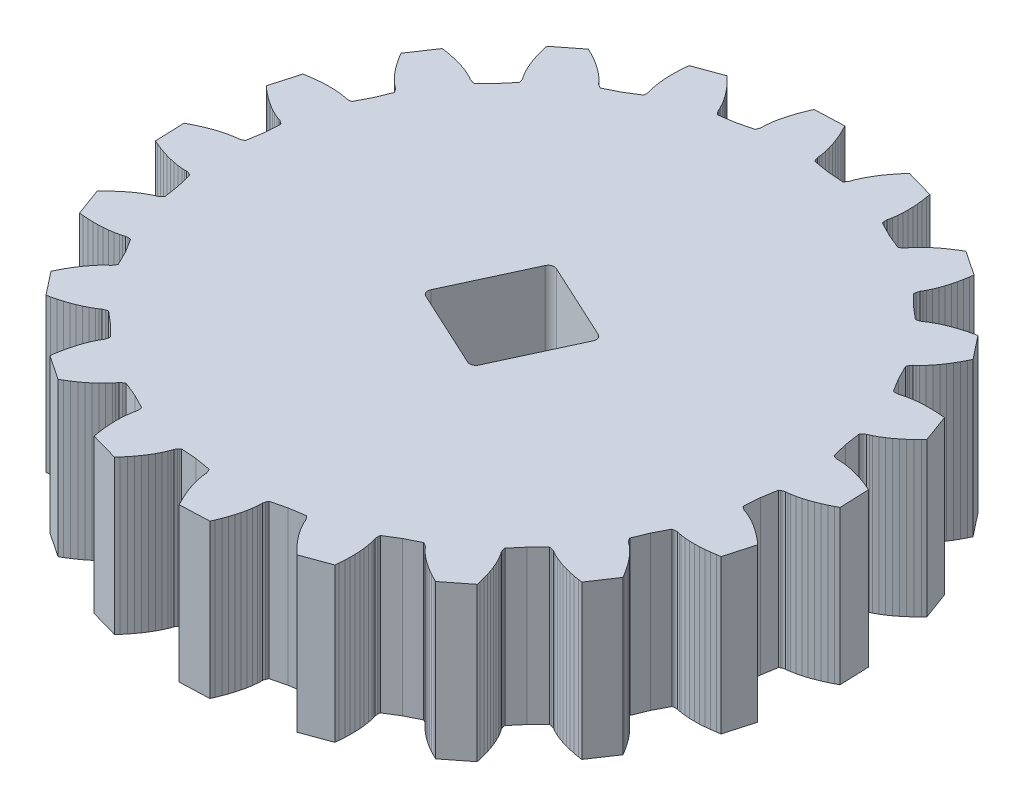
SolidWorks part; units mm, degrees
ref_plane "Front Plane" through (0, 0, 0) normal (0, 0, 1) x (1, 0, 0)
ref_plane "Top Plane" through (0, 0, 0) normal (0, 1, 0) x (1, 0, 0)
ref_plane "Right Plane" through (0, 0, 0) normal (1, 0, 0) x (0, 0, -1)
sketch "Sketch5" plane through (0, 0, 0) normal (0, 1, 0) x (1, 0, 0)
  line L0 (19.9342, 9.6525) -> (19.896, 9.1377)
  line L1 (19.896, 9.1377) -> (19.9282, 9.104)
  line L2 (19.9282, 9.104) -> (19.9619, 9.0786)
  line L3 (19.9619, 9.0786) -> (20.0304, 9.0343)
  line L4 (20.0304, 9.0343) -> (20.1028, 9.0113)
  line L5 (20.1028, 9.0113) -> (20.1744, 8.9841)
  line L6 (20.1744, 8.9841) -> (20.3158, 8.9208)
  line L7 (20.3158, 8.9208) -> (20.4552, 8.8477)
  line L8 (20.4552, 8.8477) -> (20.5926, 8.7663)
  line L9 (20.5926, 8.7663) -> (20.7283, 8.6773)
  line L10 (20.7283, 8.6773) -> (20.862, 8.5813)
  line L11 (20.862, 8.5813) -> (20.9939, 8.4788)
  line L12 (20.9939, 8.4788) -> (21.1239, 8.37)
  line L13 (21.1239, 8.37) -> (21.22, 8.2845)
  line L14 (21.22, 8.2845) -> (20.9572, 7.3582)
  line L15 (20.9572, 7.3582) -> (20.8305, 7.336)
  line L16 (20.8305, 7.336) -> (20.6628, 7.3117)
  line L17 (20.6628, 7.3117) -> (20.4967, 7.2937)
  line L18 (20.4967, 7.2937) -> (20.3325, 7.2823)
  line L19 (20.3325, 7.2823) -> (20.1703, 7.2778)
  line L20 (20.1703, 7.2778) -> (20.0105, 7.2806)
  line L21 (20.0105, 7.2806) -> (19.8536, 7.2916)
  line L22 (19.8536, 7.2916) -> (19.7, 7.312)
  line L23 (19.7, 7.312) -> (19.6248, 7.3265)
  line L24 (19.6248, 7.3265) -> (19.5511, 7.3449)
  line L25 (19.5511, 7.3449) -> (19.4696, 7.3432)
  line L26 (19.4696, 7.3432) -> (19.4275, 7.3393)
  line L27 (19.4275, 7.3393) -> (19.3824, 7.3276)
  line L28 (19.3824, 7.3276) -> (19.1446, 6.8694)
  line L29 (19.1446, 6.8694) -> (18.9491, 6.3916)
  line L30 (18.9491, 6.3916) -> (18.9694, 6.3497)
  line L31 (18.9694, 6.3497) -> (18.9936, 6.3151)
  line L32 (18.9936, 6.3151) -> (19.0451, 6.2518)
  line L33 (19.0451, 6.2518) -> (19.1068, 6.2075)
  line L34 (19.1068, 6.2075) -> (19.1665, 6.1596)
  line L35 (19.1665, 6.1596) -> (19.2814, 6.0556)
  line L36 (19.2814, 6.0556) -> (19.3914, 5.9431)
  line L37 (19.3914, 5.9431) -> (19.4969, 5.8231)
  line L38 (19.4969, 5.8231) -> (19.5984, 5.6966)
  line L39 (19.5984, 5.6966) -> (19.696, 5.564)
  line L40 (19.696, 5.564) -> (19.7898, 5.4257)
  line L41 (19.7898, 5.4257) -> (19.8797, 5.2821)
  line L42 (19.8797, 5.2821) -> (19.9447, 5.1711)
  line L43 (19.9447, 5.1711) -> (19.4086, 4.3714)
  line L44 (19.4086, 4.3714) -> (19.2812, 4.3893)
  line L45 (19.2812, 4.3893) -> (19.1141, 4.418)
  line L46 (19.1141, 4.418) -> (18.9506, 4.4523)
  line L47 (18.9506, 4.4523) -> (18.7909, 4.4922)
  line L48 (18.7909, 4.4922) -> (18.6353, 4.538)
  line L49 (18.6353, 4.538) -> (18.4843, 4.5901)
  line L50 (18.4843, 4.5901) -> (18.3384, 4.649)
  line L51 (18.3384, 4.649) -> (18.1986, 4.7159)
  line L52 (18.1986, 4.7159) -> (18.1316, 4.7529)
  line L53 (18.1316, 4.7529) -> (18.0671, 4.7932)
  line L54 (18.0671, 4.7932) -> (17.9891, 4.8167)
  line L55 (17.9891, 4.8167) -> (17.9479, 4.826)
  line L56 (17.9479, 4.826) -> (17.9014, 4.8289)
  line L57 (17.9014, 4.8289) -> (17.5336, 4.4666)
  line L58 (17.5336, 4.4666) -> (17.2001, 4.0726)
  line L59 (17.2001, 4.0726) -> (17.2064, 4.0264)
  line L60 (17.2064, 4.0264) -> (17.2187, 3.986)
  line L61 (17.2187, 3.986) -> (17.2481, 3.91)
  line L62 (17.2481, 3.91) -> (17.2931, 3.8488)
  line L63 (17.2931, 3.8488) -> (17.3351, 3.7847)
  line L64 (17.3351, 3.7847) -> (17.4123, 3.6504)
  line L65 (17.4123, 3.6504) -> (17.4821, 3.5093)
  line L66 (17.4821, 3.5093) -> (17.5454, 3.3626)
  line L67 (17.5454, 3.3626) -> (17.6028, 3.2109)
  line L68 (17.6028, 3.2109) -> (17.6546, 3.0547)
  line L69 (17.6546, 3.0547) -> (17.7011, 2.8942)
  line L70 (17.7011, 2.8942) -> (17.7423, 2.7298)
  line L71 (17.7423, 2.7298) -> (17.7698, 2.6041)
  line L72 (17.7698, 2.6041) -> (17.0127, 2.0092)
  line L73 (17.0127, 2.0092) -> (16.8971, 2.0657)
  line L74 (16.8971, 2.0657) -> (16.7471, 2.1446)
  line L75 (16.7471, 2.1446) -> (16.6022, 2.2277)
  line L76 (16.6022, 2.2277) -> (16.4626, 2.315)
  line L77 (16.4626, 2.315) -> (16.3288, 2.4066)
  line L78 (16.3288, 2.4066) -> (16.2013, 2.5029)
  line L79 (16.2013, 2.5029) -> (16.0807, 2.604)
  line L80 (16.0807, 2.604) -> (15.9684, 2.7108)
  line L81 (15.9684, 2.7108) -> (15.9161, 2.7667)
  line L82 (15.9161, 2.7667) -> (15.8673, 2.8249)
  line L83 (15.8673, 2.8249) -> (15.8003, 2.8715)
  line L84 (15.8003, 2.8715) -> (15.764, 2.893)
  line L85 (15.764, 2.893) -> (15.7207, 2.9101)
  line L86 (15.7207, 2.9101) -> (15.2589, 2.6792)
  line L87 (15.2589, 2.6792) -> (14.82, 2.4075)
  line L88 (14.82, 2.4075) -> (14.8117, 2.3617)
  line L89 (14.8117, 2.3617) -> (14.811, 2.3194)
  line L90 (14.811, 2.3194) -> (14.8155, 2.238)
  line L91 (14.8155, 2.238) -> (14.8393, 2.1659)
  line L92 (14.8393, 2.1659) -> (14.8594, 2.092)
  line L93 (14.8594, 2.092) -> (14.8913, 1.9404)
  line L94 (14.8913, 1.9404) -> (14.9141, 1.7847)
  line L95 (14.9141, 1.7847) -> (14.929, 1.6256)
  line L96 (14.929, 1.6256) -> (14.9367, 1.4636)
  line L97 (14.9367, 1.4636) -> (14.9377, 1.299)
  line L98 (14.9377, 1.299) -> (14.9323, 1.132)
  line L99 (14.9323, 1.132) -> (14.9207, 0.9629)
  line L100 (14.9207, 0.9629) -> (14.908, 0.8349)
  line L101 (14.908, 0.8349) -> (14.0042, 0.503)
  line L102 (14.0042, 0.503) -> (13.9117, 0.5925)
  line L103 (13.9117, 0.5925) -> (13.7934, 0.7139)
  line L104 (13.7934, 0.7139) -> (13.6813, 0.8377)
  line L105 (13.6813, 0.8377) -> (13.5755, 0.9638)
  line L106 (13.5755, 0.9638) -> (13.4766, 1.0924)
  line L107 (13.4766, 1.0924) -> (13.385, 1.2233)
  line L108 (13.385, 1.2233) -> (13.3016, 1.3568)
  line L109 (13.3016, 1.3568) -> (13.2278, 1.493)
  line L110 (13.2278, 1.493) -> (13.1953, 1.5623)
  line L111 (13.1953, 1.5623) -> (13.1669, 1.6328)
  line L112 (13.1669, 1.6328) -> (13.1176, 1.6977)
  line L113 (13.1176, 1.6977) -> (13.0897, 1.7294)
  line L114 (13.0897, 1.7294) -> (13.0538, 1.7591)
  line L115 (13.0538, 1.7591) -> (12.5433, 1.6822)
  line L116 (12.5433, 1.6822) -> (12.0419, 1.5595)
  line L117 (12.0419, 1.5595) -> (12.0199, 1.5184)
  line L118 (12.0199, 1.5184) -> (12.0061, 1.4785)
  line L119 (12.0061, 1.4785) -> (11.9852, 1.3996)
  line L120 (11.9852, 1.3996) -> (11.9856, 1.3237)
  line L121 (11.9856, 1.3237) -> (11.9819, 1.2472)
  line L122 (11.9819, 1.2472) -> (11.9654, 1.0932)
  line L123 (11.9654, 1.0932) -> (11.9389, 0.938)
  line L124 (11.9389, 0.938) -> (11.9039, 0.7821)
  line L125 (11.9039, 0.7821) -> (11.8612, 0.6256)
  line L126 (11.8612, 0.6256) -> (11.8113, 0.4688)
  line L127 (11.8113, 0.4688) -> (11.7546, 0.3116)
  line L128 (11.7546, 0.3116) -> (11.6913, 0.1544)
  line L129 (11.6913, 0.1544) -> (11.6396, 0.0366)
  line L130 (11.6396, 0.0366) -> (10.6775, 0.0003)
  line L131 (10.6775, 0.0003) -> (10.6172, 0.1139)
  line L132 (10.6172, 0.1139) -> (10.5422, 0.2659)
  line L133 (10.5422, 0.2659) -> (10.4738, 0.4183)
  line L134 (10.4738, 0.4183) -> (10.4122, 0.571)
  line L135 (10.4122, 0.571) -> (10.3578, 0.7238)
  line L136 (10.3578, 0.7238) -> (10.3111, 0.8766)
  line L137 (10.3111, 0.8766) -> (10.2731, 1.0293)
  line L138 (10.2731, 1.0293) -> (10.245, 1.1817)
  line L139 (10.245, 1.1817) -> (10.2356, 1.2577)
  line L140 (10.2356, 1.2577) -> (10.2303, 1.3335)
  line L141 (10.2303, 1.3335) -> (10.2035, 1.4105)
  line L142 (10.2035, 1.4105) -> (10.1867, 1.4492)
  line L143 (10.1867, 1.4492) -> (10.1617, 1.4885)
  line L144 (10.1617, 1.4885) -> (9.6525, 1.5732)
  line L145 (9.6525, 1.5732) -> (9.1377, 1.6114)
  line L146 (9.1377, 1.6114) -> (9.104, 1.5791)
  line L147 (9.104, 1.5791) -> (9.0786, 1.5454)
  line L148 (9.0786, 1.5454) -> (9.0343, 1.4769)
  line L149 (9.0343, 1.4769) -> (9.0113, 1.4045)
  line L150 (9.0113, 1.4045) -> (8.9841, 1.3329)
  line L151 (8.9841, 1.3329) -> (8.9208, 1.1915)
  line L152 (8.9208, 1.1915) -> (8.8477, 1.0522)
  line L153 (8.8477, 1.0522) -> (8.7663, 0.9147)
  line L154 (8.7663, 0.9147) -> (8.6773, 0.7791)
  line L155 (8.6773, 0.7791) -> (8.5813, 0.6453)
  line L156 (8.5813, 0.6453) -> (8.4788, 0.5134)
  line L157 (8.4788, 0.5134) -> (8.37, 0.3835)
  line L158 (8.37, 0.3835) -> (8.2845, 0.2873)
  line L159 (8.2845, 0.2873) -> (7.3582, 0.5501)
  line L160 (7.3582, 0.5501) -> (7.336, 0.6769)
  line L161 (7.336, 0.6769) -> (7.3117, 0.8446)
  line L162 (7.3117, 0.8446) -> (7.2937, 1.0107)
  line L163 (7.2937, 1.0107) -> (7.2823, 1.1749)
  line L164 (7.2823, 1.1749) -> (7.2778, 1.337)
  line L165 (7.2778, 1.337) -> (7.2806, 1.4968)
  line L166 (7.2806, 1.4968) -> (7.2916, 1.6538)
  line L167 (7.2916, 1.6538) -> (7.312, 1.8074)
  line L168 (7.312, 1.8074) -> (7.3265, 1.8825)
  line L169 (7.3265, 1.8825) -> (7.3449, 1.9563)
  line L170 (7.3449, 1.9563) -> (7.3432, 2.0378)
  line L171 (7.3432, 2.0378) -> (7.3393, 2.0798)
  line L172 (7.3393, 2.0798) -> (7.3276, 2.1249)
  line L173 (7.3276, 2.1249) -> (6.8694, 2.3628)
  line L174 (6.8694, 2.3628) -> (6.3916, 2.5582)
  line L175 (6.3916, 2.5582) -> (6.3497, 2.5379)
  line L176 (6.3497, 2.5379) -> (6.3151, 2.5137)
  line L177 (6.3151, 2.5137) -> (6.2518, 2.4622)
  line L178 (6.2518, 2.4622) -> (6.2075, 2.4005)
  line L179 (6.2075, 2.4005) -> (6.1596, 2.3408)
  line L180 (6.1596, 2.3408) -> (6.0556, 2.2259)
  line L181 (6.0556, 2.2259) -> (5.9431, 2.116)
  line L182 (5.9431, 2.116) -> (5.8231, 2.0104)
  line L183 (5.8231, 2.0104) -> (5.6966, 1.9089)
  line L184 (5.6966, 1.9089) -> (5.564, 1.8113)
  line L185 (5.564, 1.8113) -> (5.4257, 1.7176)
  line L186 (5.4257, 1.7176) -> (5.2821, 1.6276)
  line L187 (5.2821, 1.6276) -> (5.1711, 1.5626)
  line L188 (5.1711, 1.5626) -> (4.3714, 2.0987)
  line L189 (4.3714, 2.0987) -> (4.3893, 2.2262)
  line L190 (4.3893, 2.2262) -> (4.418, 2.3932)
  line L191 (4.418, 2.3932) -> (4.4523, 2.5567)
  line L192 (4.4523, 2.5567) -> (4.4922, 2.7164)
  line L193 (4.4922, 2.7164) -> (4.538, 2.872)
  line L194 (4.538, 2.872) -> (4.5901, 3.0231)
  line L195 (4.5901, 3.0231) -> (4.649, 3.169)
  line L196 (4.649, 3.169) -> (4.7159, 3.3087)
  line L197 (4.7159, 3.3087) -> (4.7529, 3.3758)
  line L198 (4.7529, 3.3758) -> (4.7932, 3.4402)
  line L199 (4.7932, 3.4402) -> (4.8167, 3.5183)
  line L200 (4.8167, 3.5183) -> (4.826, 3.5595)
  line L201 (4.826, 3.5595) -> (4.8289, 3.606)
  line L202 (4.8289, 3.606) -> (4.4666, 3.9737)
  line L203 (4.4666, 3.9737) -> (4.0726, 4.3073)
  line L204 (4.0726, 4.3073) -> (4.0264, 4.3009)
  line L205 (4.0264, 4.3009) -> (3.986, 4.2886)
  line L206 (3.986, 4.2886) -> (3.91, 4.2592)
  line L207 (3.91, 4.2592) -> (3.8488, 4.2142)
  line L208 (3.8488, 4.2142) -> (3.7847, 4.1723)
  line L209 (3.7847, 4.1723) -> (3.6504, 4.0951)
  line L210 (3.6504, 4.0951) -> (3.5093, 4.0253)
  line L211 (3.5093, 4.0253) -> (3.3626, 3.9619)
  line L212 (3.3626, 3.9619) -> (3.2109, 3.9045)
  line L213 (3.2109, 3.9045) -> (3.0547, 3.8527)
  line L214 (3.0547, 3.8527) -> (2.8942, 3.8063)
  line L215 (2.8942, 3.8063) -> (2.7298, 3.7651)
  line L216 (2.7298, 3.7651) -> (2.6041, 3.7376)
  line L217 (2.6041, 3.7376) -> (2.0092, 4.4946)
  line L218 (2.0092, 4.4946) -> (2.0657, 4.6102)
  line L219 (2.0657, 4.6102) -> (2.1446, 4.7602)
  line L220 (2.1446, 4.7602) -> (2.2277, 4.9051)
  line L221 (2.2277, 4.9051) -> (2.315, 5.0447)
  line L222 (2.315, 5.0447) -> (2.4066, 5.1785)
  line L223 (2.4066, 5.1785) -> (2.5029, 5.3061)
  line L224 (2.5029, 5.3061) -> (2.604, 5.4266)
  line L225 (2.604, 5.4266) -> (2.7108, 5.5389)
  line L226 (2.7108, 5.5389) -> (2.7667, 5.5912)
  line L227 (2.7667, 5.5912) -> (2.8249, 5.64)
  line L228 (2.8249, 5.64) -> (2.8715, 5.707)
  line L229 (2.8715, 5.707) -> (2.893, 5.7433)
  line L230 (2.893, 5.7433) -> (2.9101, 5.7867)
  line L231 (2.9101, 5.7867) -> (2.6792, 6.2484)
  line L232 (2.6792, 6.2484) -> (2.4075, 6.6874)
  line L233 (2.4075, 6.6874) -> (2.3617, 6.6956)
  line L234 (2.3617, 6.6956) -> (2.3194, 6.6963)
  line L235 (2.3194, 6.6963) -> (2.238, 6.6919)
  line L236 (2.238, 6.6919) -> (2.1659, 6.668)
  line L237 (2.1659, 6.668) -> (2.092, 6.6479)
  line L238 (2.092, 6.6479) -> (1.9404, 6.616)
  line L239 (1.9404, 6.616) -> (1.7847, 6.5932)
  line L240 (1.7847, 6.5932) -> (1.6256, 6.5783)
  line L241 (1.6256, 6.5783) -> (1.4636, 6.5706)
  line L242 (1.4636, 6.5706) -> (1.299, 6.5696)
  line L243 (1.299, 6.5696) -> (1.132, 6.575)
  line L244 (1.132, 6.575) -> (0.9629, 6.5866)
  line L245 (0.9629, 6.5866) -> (0.8349, 6.5993)
  line L246 (0.8349, 6.5993) -> (0.503, 7.5031)
  line L247 (0.503, 7.5031) -> (0.5925, 7.5957)
  line L248 (0.5925, 7.5957) -> (0.7139, 7.7139)
  line L249 (0.7139, 7.7139) -> (0.8377, 7.8261)
  line L250 (0.8377, 7.8261) -> (0.9638, 7.9318)
  line L251 (0.9638, 7.9318) -> (1.0924, 8.0308)
  line L252 (1.0924, 8.0308) -> (1.2233, 8.1224)
  line L253 (1.2233, 8.1224) -> (1.3568, 8.2057)
  line L254 (1.3568, 8.2057) -> (1.493, 8.2795)
  line L255 (1.493, 8.2795) -> (1.5623, 8.312)
  line L256 (1.5623, 8.312) -> (1.6328, 8.3405)
  line L257 (1.6328, 8.3405) -> (1.6977, 8.3897)
  line L258 (1.6977, 8.3897) -> (1.7294, 8.4176)
  line L259 (1.7294, 8.4176) -> (1.7591, 8.4536)
  line L260 (1.7591, 8.4536) -> (1.6822, 8.9641)
  line L261 (1.6822, 8.9641) -> (1.5595, 9.4655)
  line L262 (1.5595, 9.4655) -> (1.5184, 9.4875)
  line L263 (1.5184, 9.4875) -> (1.4785, 9.5012)
  line L264 (1.4785, 9.5012) -> (1.3996, 9.5222)
  line L265 (1.3996, 9.5222) -> (1.3237, 9.5217)
  line L266 (1.3237, 9.5217) -> (1.2472, 9.5254)
  line L267 (1.2472, 9.5254) -> (1.0932, 9.542)
  line L268 (1.0932, 9.542) -> (0.938, 9.5684)
  line L269 (0.938, 9.5684) -> (0.7821, 9.6034)
  line L270 (0.7821, 9.6034) -> (0.6256, 9.6461)
  line L271 (0.6256, 9.6461) -> (0.4688, 9.696)
  line L272 (0.4688, 9.696) -> (0.3116, 9.7528)
  line L273 (0.3116, 9.7528) -> (0.1544, 9.8161)
  line L274 (0.1544, 9.8161) -> (0.0366, 9.8677)
  line L275 (0.0366, 9.8677) -> (0.0003, 10.8298)
  line L276 (0.0003, 10.8298) -> (0.1139, 10.8902)
  line L277 (0.1139, 10.8902) -> (0.2659, 10.9651)
  line L278 (0.2659, 10.9651) -> (0.4183, 11.0336)
  line L279 (0.4183, 11.0336) -> (0.571, 11.0952)
  line L280 (0.571, 11.0952) -> (0.7238, 11.1495)
  line L281 (0.7238, 11.1495) -> (0.8766, 11.1962)
  line L282 (0.8766, 11.1962) -> (1.0293, 11.2342)
  line L283 (1.0293, 11.2342) -> (1.1817, 11.2623)
  line L284 (1.1817, 11.2623) -> (1.2577, 11.2718)
  line L285 (1.2577, 11.2718) -> (1.3335, 11.2771)
  line L286 (1.3335, 11.2771) -> (1.4105, 11.3039)
  line L287 (1.4105, 11.3039) -> (1.4492, 11.3206)
  line L288 (1.4492, 11.3206) -> (1.4885, 11.3456)
  line L289 (1.4885, 11.3456) -> (1.5732, 11.8549)
  line L290 (1.5732, 11.8549) -> (1.6114, 12.3697)
  line L291 (1.6114, 12.3697) -> (1.5791, 12.4033)
  line L292 (1.5791, 12.4033) -> (1.5454, 12.4287)
  line L293 (1.5454, 12.4287) -> (1.4769, 12.473)
  line L294 (1.4769, 12.473) -> (1.4045, 12.4961)
  line L295 (1.4045, 12.4961) -> (1.3329, 12.5232)
  line L296 (1.3329, 12.5232) -> (1.1915, 12.5865)
  line L297 (1.1915, 12.5865) -> (1.0522, 12.6596)
  line L298 (1.0522, 12.6596) -> (0.9147, 12.7411)
  line L299 (0.9147, 12.7411) -> (0.7791, 12.8301)
  line L300 (0.7791, 12.8301) -> (0.6453, 12.926)
  line L301 (0.6453, 12.926) -> (0.5134, 13.0285)
  line L302 (0.5134, 13.0285) -> (0.3835, 13.1373)
  line L303 (0.3835, 13.1373) -> (0.2873, 13.2228)
  line L304 (0.2873, 13.2228) -> (0.5501, 14.1491)
  line L305 (0.5501, 14.1491) -> (0.6769, 14.1714)
  line L306 (0.6769, 14.1714) -> (0.8446, 14.1957)
  line L307 (0.8446, 14.1957) -> (1.0107, 14.2137)
  line L308 (1.0107, 14.2137) -> (1.1749, 14.2251)
  line L309 (1.1749, 14.2251) -> (1.337, 14.2296)
  line L310 (1.337, 14.2296) -> (1.4968, 14.2267)
  line L311 (1.4968, 14.2267) -> (1.6538, 14.2157)
  line L312 (1.6538, 14.2157) -> (1.8074, 14.1953)
  line L313 (1.8074, 14.1953) -> (1.8825, 14.1808)
  line L314 (1.8825, 14.1808) -> (1.9563, 14.1625)
  line L315 (1.9563, 14.1625) -> (2.0378, 14.1642)
  line L316 (2.0378, 14.1642) -> (2.0798, 14.1681)
  line L317 (2.0798, 14.1681) -> (2.1249, 14.1798)
  line L318 (2.1249, 14.1798) -> (2.3628, 14.6379)
  line L319 (2.3628, 14.6379) -> (2.5582, 15.1157)
  line L320 (2.5582, 15.1157) -> (2.5379, 15.1577)
  line L321 (2.5379, 15.1577) -> (2.5137, 15.1922)
  line L322 (2.5137, 15.1922) -> (2.4622, 15.2555)
  line L323 (2.4622, 15.2555) -> (2.4005, 15.2998)
  line L324 (2.4005, 15.2998) -> (2.3408, 15.3478)
  line L325 (2.3408, 15.3478) -> (2.2259, 15.4517)
  line L326 (2.2259, 15.4517) -> (2.116, 15.5643)
  line L327 (2.116, 15.5643) -> (2.0104, 15.6842)
  line L328 (2.0104, 15.6842) -> (1.9089, 15.8108)
  line L329 (1.9089, 15.8108) -> (1.8113, 15.9434)
  line L330 (1.8113, 15.9434) -> (1.7176, 16.0816)
  line L331 (1.7176, 16.0816) -> (1.6276, 16.2252)
  line L332 (1.6276, 16.2252) -> (1.5626, 16.3363)
  line L333 (1.5626, 16.3363) -> (2.0987, 17.136)
  line L334 (2.0987, 17.136) -> (2.2262, 17.118)
  line L335 (2.2262, 17.118) -> (2.3932, 17.0893)
  line L336 (2.3932, 17.0893) -> (2.5567, 17.0551)
  line L337 (2.5567, 17.0551) -> (2.7164, 17.0152)
  line L338 (2.7164, 17.0152) -> (2.872, 16.9694)
  line L339 (2.872, 16.9694) -> (3.0231, 16.9172)
  line L340 (3.0231, 16.9172) -> (3.169, 16.8583)
  line L341 (3.169, 16.8583) -> (3.3087, 16.7914)
  line L342 (3.3087, 16.7914) -> (3.3758, 16.7544)
  line L343 (3.3758, 16.7544) -> (3.4402, 16.7142)
  line L344 (3.4402, 16.7142) -> (3.5183, 16.6906)
  line L345 (3.5183, 16.6906) -> (3.5595, 16.6813)
  line L346 (3.5595, 16.6813) -> (3.606, 16.6785)
  line L347 (3.606, 16.6785) -> (3.9737, 17.0407)
  line L348 (3.9737, 17.0407) -> (4.3073, 17.4348)
  line L349 (4.3073, 17.4348) -> (4.3009, 17.4809)
  line L350 (4.3009, 17.4809) -> (4.2886, 17.5213)
  line L351 (4.2886, 17.5213) -> (4.2592, 17.5974)
  line L352 (4.2592, 17.5974) -> (4.2142, 17.6586)
  line L353 (4.2142, 17.6586) -> (4.1723, 17.7226)
  line L354 (4.1723, 17.7226) -> (4.0951, 17.857)
  line L355 (4.0951, 17.857) -> (4.0253, 17.998)
  line L356 (4.0253, 17.998) -> (3.9619, 18.1447)
  line L357 (3.9619, 18.1447) -> (3.9045, 18.2964)
  line L358 (3.9045, 18.2964) -> (3.8527, 18.4527)
  line L359 (3.8527, 18.4527) -> (3.8063, 18.6131)
  line L360 (3.8063, 18.6131) -> (3.7651, 18.7775)
  line L361 (3.7651, 18.7775) -> (3.7376, 18.9032)
  line L362 (3.7376, 18.9032) -> (4.4946, 19.4981)
  line L363 (4.4946, 19.4981) -> (4.6102, 19.4417)
  line L364 (4.6102, 19.4417) -> (4.7602, 19.3627)
  line L365 (4.7602, 19.3627) -> (4.9051, 19.2797)
  line L366 (4.9051, 19.2797) -> (5.0447, 19.1924)
  line L367 (5.0447, 19.1924) -> (5.1785, 19.1007)
  line L368 (5.1785, 19.1007) -> (5.3061, 19.0045)
  line L369 (5.3061, 19.0045) -> (5.4266, 18.9033)
  line L370 (5.4266, 18.9033) -> (5.5389, 18.7965)
  line L371 (5.5389, 18.7965) -> (5.5912, 18.7406)
  line L372 (5.5912, 18.7406) -> (5.64, 18.6824)
  line L373 (5.64, 18.6824) -> (5.707, 18.6359)
  line L374 (5.707, 18.6359) -> (5.7433, 18.6144)
  line L375 (5.7433, 18.6144) -> (5.7867, 18.5973)
  line L376 (5.7867, 18.5973) -> (6.2484, 18.8281)
  line L377 (6.2484, 18.8281) -> (6.6874, 19.0998)
  line L378 (6.6874, 19.0998) -> (6.6956, 19.1457)
  line L379 (6.6956, 19.1457) -> (6.6963, 19.1879)
  line L380 (6.6963, 19.1879) -> (6.6919, 19.2693)
  line L381 (6.6919, 19.2693) -> (6.668, 19.3414)
  line L382 (6.668, 19.3414) -> (6.6479, 19.4153)
  line L383 (6.6479, 19.4153) -> (6.616, 19.5669)
  line L384 (6.616, 19.5669) -> (6.5932, 19.7226)
  line L385 (6.5932, 19.7226) -> (6.5783, 19.8817)
  line L386 (6.5783, 19.8817) -> (6.5706, 20.0437)
  line L387 (6.5706, 20.0437) -> (6.5696, 20.2084)
  line L388 (6.5696, 20.2084) -> (6.575, 20.3753)
  line L389 (6.575, 20.3753) -> (6.5866, 20.5444)
  line L390 (6.5866, 20.5444) -> (6.5993, 20.6725)
  line L391 (6.5993, 20.6725) -> (7.5031, 21.0043)
  line L392 (7.5031, 21.0043) -> (7.5957, 20.9149)
  line L393 (7.5957, 20.9149) -> (7.7139, 20.7935)
  line L394 (7.7139, 20.7935) -> (7.8261, 20.6697)
  line L395 (7.8261, 20.6697) -> (7.9318, 20.5435)
  line L396 (7.9318, 20.5435) -> (8.0308, 20.415)
  line L397 (8.0308, 20.415) -> (8.1224, 20.284)
  line L398 (8.1224, 20.284) -> (8.2057, 20.1506)
  line L399 (8.2057, 20.1506) -> (8.2795, 20.0143)
  line L400 (8.2795, 20.0143) -> (8.312, 19.945)
  line L401 (8.312, 19.945) -> (8.3405, 19.8746)
  line L402 (8.3405, 19.8746) -> (8.3897, 19.8096)
  line L403 (8.3897, 19.8096) -> (8.4176, 19.7779)
  line L404 (8.4176, 19.7779) -> (8.4536, 19.7482)
  line L405 (8.4536, 19.7482) -> (8.9641, 19.8252)
  line L406 (8.9641, 19.8252) -> (9.4655, 19.9479)
  line L407 (9.4655, 19.9479) -> (9.4875, 19.989)
  line L408 (9.4875, 19.989) -> (9.5012, 20.0289)
  line L409 (9.5012, 20.0289) -> (9.5222, 20.1077)
  line L410 (9.5222, 20.1077) -> (9.5217, 20.1837)
  line L411 (9.5217, 20.1837) -> (9.5254, 20.2601)
  line L412 (9.5254, 20.2601) -> (9.542, 20.4142)
  line L413 (9.542, 20.4142) -> (9.5684, 20.5693)
  line L414 (9.5684, 20.5693) -> (9.6034, 20.7252)
  line L415 (9.6034, 20.7252) -> (9.6461, 20.8817)
  line L416 (9.6461, 20.8817) -> (9.696, 21.0386)
  line L417 (9.696, 21.0386) -> (9.7528, 21.1957)
  line L418 (9.7528, 21.1957) -> (9.8161, 21.3529)
  line L419 (9.8161, 21.3529) -> (9.8677, 21.4708)
  line L420 (9.8677, 21.4708) -> (10.8298, 21.5071)
  line L421 (10.8298, 21.5071) -> (10.8902, 21.3934)
  line L422 (10.8902, 21.3934) -> (10.9651, 21.2414)
  line L423 (10.9651, 21.2414) -> (11.0336, 21.089)
  line L424 (11.0336, 21.089) -> (11.0952, 20.9364)
  line L425 (11.0952, 20.9364) -> (11.1495, 20.7835)
  line L426 (11.1495, 20.7835) -> (11.1962, 20.6307)
  line L427 (11.1962, 20.6307) -> (11.2342, 20.478)
  line L428 (11.2342, 20.478) -> (11.2623, 20.3256)
  line L429 (11.2623, 20.3256) -> (11.2718, 20.2497)
  line L430 (11.2718, 20.2497) -> (11.2771, 20.1739)
  line L431 (11.2771, 20.1739) -> (11.3039, 20.0969)
  line L432 (11.3039, 20.0969) -> (11.3206, 20.0581)
  line L433 (11.3206, 20.0581) -> (11.3456, 20.0188)
  line L434 (11.3456, 20.0188) -> (11.8549, 19.9342)
  line L435 (11.8549, 19.9342) -> (12.3697, 19.896)
  line L436 (12.3697, 19.896) -> (12.4033, 19.9282)
  line L437 (12.4033, 19.9282) -> (12.4287, 19.9619)
  line L438 (12.4287, 19.9619) -> (12.473, 20.0304)
  line L439 (12.473, 20.0304) -> (12.4961, 20.1028)
  line L440 (12.4961, 20.1028) -> (12.5232, 20.1744)
  line L441 (12.5232, 20.1744) -> (12.5865, 20.3158)
  line L442 (12.5865, 20.3158) -> (12.6596, 20.4552)
  line L443 (12.6596, 20.4552) -> (12.7411, 20.5926)
  line L444 (12.7411, 20.5926) -> (12.8301, 20.7283)
  line L445 (12.8301, 20.7283) -> (12.926, 20.862)
  line L446 (12.926, 20.862) -> (13.0285, 20.9939)
  line L447 (13.0285, 20.9939) -> (13.1373, 21.1239)
  line L448 (13.1373, 21.1239) -> (13.2228, 21.22)
  line L449 (13.2228, 21.22) -> (14.1491, 20.9572)
  line L450 (14.1491, 20.9572) -> (14.1714, 20.8305)
  line L451 (14.1714, 20.8305) -> (14.1957, 20.6628)
  line L452 (14.1957, 20.6628) -> (14.2137, 20.4967)
  line L453 (14.2137, 20.4967) -> (14.2251, 20.3325)
  line L454 (14.2251, 20.3325) -> (14.2296, 20.1703)
  line L455 (14.2296, 20.1703) -> (14.2267, 20.0105)
  line L456 (14.2267, 20.0105) -> (14.2157, 19.8536)
  line L457 (14.2157, 19.8536) -> (14.1953, 19.7)
  line L458 (14.1953, 19.7) -> (14.1808, 19.6248)
  line L459 (14.1808, 19.6248) -> (14.1625, 19.5511)
  line L460 (14.1625, 19.5511) -> (14.1642, 19.4696)
  line L461 (14.1642, 19.4696) -> (14.1681, 19.4275)
  line L462 (14.1681, 19.4275) -> (14.1798, 19.3824)
  line L463 (14.1798, 19.3824) -> (14.6379, 19.1446)
  line L464 (14.6379, 19.1446) -> (15.1157, 18.9491)
  line L465 (15.1157, 18.9491) -> (15.1577, 18.9694)
  line L466 (15.1577, 18.9694) -> (15.1922, 18.9936)
  line L467 (15.1922, 18.9936) -> (15.2555, 19.0451)
  line L468 (15.2555, 19.0451) -> (15.2998, 19.1068)
  line L469 (15.2998, 19.1068) -> (15.3478, 19.1665)
  line L470 (15.3478, 19.1665) -> (15.4517, 19.2814)
  line L471 (15.4517, 19.2814) -> (15.5643, 19.3914)
  line L472 (15.5643, 19.3914) -> (15.6842, 19.4969)
  line L473 (15.6842, 19.4969) -> (15.8108, 19.5984)
  line L474 (15.8108, 19.5984) -> (15.9434, 19.696)
  line L475 (15.9434, 19.696) -> (16.0816, 19.7898)
  line L476 (16.0816, 19.7898) -> (16.2252, 19.8797)
  line L477 (16.2252, 19.8797) -> (16.3363, 19.9447)
  line L478 (16.3363, 19.9447) -> (17.136, 19.4086)
  line L479 (17.136, 19.4086) -> (17.118, 19.2812)
  line L480 (17.118, 19.2812) -> (17.0893, 19.1141)
  line L481 (17.0893, 19.1141) -> (17.0551, 18.9506)
  line L482 (17.0551, 18.9506) -> (17.0152, 18.7909)
  line L483 (17.0152, 18.7909) -> (16.9694, 18.6353)
  line L484 (16.9694, 18.6353) -> (16.9172, 18.4843)
  line L485 (16.9172, 18.4843) -> (16.8583, 18.3384)
  line L486 (16.8583, 18.3384) -> (16.7914, 18.1986)
  line L487 (16.7914, 18.1986) -> (16.7544, 18.1316)
  line L488 (16.7544, 18.1316) -> (16.7142, 18.0671)
  line L489 (16.7142, 18.0671) -> (16.6906, 17.9891)
  line L490 (16.6906, 17.9891) -> (16.6813, 17.9479)
  line L491 (16.6813, 17.9479) -> (16.6785, 17.9014)
  line L492 (16.6785, 17.9014) -> (17.0407, 17.5336)
  line L493 (17.0407, 17.5336) -> (17.4348, 17.2001)
  line L494 (17.4348, 17.2001) -> (17.4809, 17.2064)
  line L495 (17.4809, 17.2064) -> (17.5213, 17.2187)
  line L496 (17.5213, 17.2187) -> (17.5974, 17.2481)
  line L497 (17.5974, 17.2481) -> (17.6586, 17.2931)
  line L498 (17.6586, 17.2931) -> (17.7226, 17.3351)
  line L499 (17.7226, 17.3351) -> (17.857, 17.4123)
  line L500 (17.857, 17.4123) -> (17.998, 17.4821)
  line L501 (17.998, 17.4821) -> (18.1447, 17.5454)
  line L502 (18.1447, 17.5454) -> (18.2964, 17.6028)
  line L503 (18.2964, 17.6028) -> (18.4527, 17.6546)
  line L504 (18.4527, 17.6546) -> (18.6131, 17.7011)
  line L505 (18.6131, 17.7011) -> (18.7775, 17.7423)
  line L506 (18.7775, 17.7423) -> (18.9032, 17.7698)
  line L507 (18.9032, 17.7698) -> (19.4981, 17.0127)
  line L508 (19.4981, 17.0127) -> (19.4417, 16.8971)
  line L509 (19.4417, 16.8971) -> (19.3627, 16.7471)
  line L510 (19.3627, 16.7471) -> (19.2797, 16.6022)
  line L511 (19.2797, 16.6022) -> (19.1924, 16.4626)
  line L512 (19.1924, 16.4626) -> (19.1007, 16.3288)
  line L513 (19.1007, 16.3288) -> (19.0045, 16.2013)
  line L514 (19.0045, 16.2013) -> (18.9033, 16.0807)
  line L515 (18.9033, 16.0807) -> (18.7965, 15.9684)
  line L516 (18.7965, 15.9684) -> (18.7406, 15.9161)
  line L517 (18.7406, 15.9161) -> (18.6824, 15.8673)
  line L518 (18.6824, 15.8673) -> (18.6359, 15.8003)
  line L519 (18.6359, 15.8003) -> (18.6144, 15.764)
  line L520 (18.6144, 15.764) -> (18.5973, 15.7207)
  line L521 (18.5973, 15.7207) -> (18.8281, 15.2589)
  line L522 (18.8281, 15.2589) -> (19.0998, 14.82)
  line L523 (19.0998, 14.82) -> (19.1457, 14.8117)
  line L524 (19.1457, 14.8117) -> (19.1879, 14.811)
  line L525 (19.1879, 14.811) -> (19.2693, 14.8155)
  line L526 (19.2693, 14.8155) -> (19.3414, 14.8393)
  line L527 (19.3414, 14.8393) -> (19.4153, 14.8594)
  line L528 (19.4153, 14.8594) -> (19.5669, 14.8913)
  line L529 (19.5669, 14.8913) -> (19.7226, 14.9141)
  line L530 (19.7226, 14.9141) -> (19.8817, 14.929)
  line L531 (19.8817, 14.929) -> (20.0437, 14.9367)
  line L532 (20.0437, 14.9367) -> (20.2084, 14.9377)
  line L533 (20.2084, 14.9377) -> (20.3753, 14.9323)
  line L534 (20.3753, 14.9323) -> (20.5444, 14.9207)
  line L535 (20.5444, 14.9207) -> (20.6725, 14.908)
  line L536 (20.6725, 14.908) -> (21.0043, 14.0042)
  line L537 (21.0043, 14.0042) -> (20.9149, 13.9117)
  line L538 (20.9149, 13.9117) -> (20.7935, 13.7934)
  line L539 (20.7935, 13.7934) -> (20.6697, 13.6813)
  line L540 (20.6697, 13.6813) -> (20.5435, 13.5755)
  line L541 (20.5435, 13.5755) -> (20.415, 13.4766)
  line L542 (20.415, 13.4766) -> (20.284, 13.385)
  line L543 (20.284, 13.385) -> (20.1506, 13.3016)
  line L544 (20.1506, 13.3016) -> (20.0143, 13.2278)
  line L545 (20.0143, 13.2278) -> (19.945, 13.1953)
  line L546 (19.945, 13.1953) -> (19.8746, 13.1669)
  line L547 (19.8746, 13.1669) -> (19.8096, 13.1176)
  line L548 (19.8096, 13.1176) -> (19.7779, 13.0897)
  line L549 (19.7779, 13.0897) -> (19.7482, 13.0538)
  line L550 (19.7482, 13.0538) -> (19.8252, 12.5433)
  line L551 (19.8252, 12.5433) -> (19.9479, 12.0419)
  line L552 (19.9479, 12.0419) -> (19.989, 12.0199)
  line L553 (19.989, 12.0199) -> (20.0289, 12.0061)
  line L554 (20.0289, 12.0061) -> (20.1077, 11.9852)
  line L555 (20.1077, 11.9852) -> (20.1837, 11.9856)
  line L556 (20.1837, 11.9856) -> (20.2601, 11.9819)
  line L557 (20.2601, 11.9819) -> (20.4142, 11.9654)
  line L558 (20.4142, 11.9654) -> (20.5693, 11.9389)
  line L559 (20.5693, 11.9389) -> (20.7252, 11.9039)
  line L560 (20.7252, 11.9039) -> (20.8817, 11.8612)
  line L561 (20.8817, 11.8612) -> (21.0386, 11.8113)
  line L562 (21.0386, 11.8113) -> (21.1957, 11.7546)
  line L563 (21.1957, 11.7546) -> (21.3529, 11.6913)
  line L564 (21.3529, 11.6913) -> (21.4708, 11.6396)
  line L565 (21.4708, 11.6396) -> (21.5071, 10.6775)
  line L566 (21.5071, 10.6775) -> (21.3934, 10.6172)
  line L567 (21.3934, 10.6172) -> (21.2414, 10.5422)
  line L568 (21.2414, 10.5422) -> (21.089, 10.4738)
  line L569 (21.089, 10.4738) -> (20.9364, 10.4122)
  line L570 (20.9364, 10.4122) -> (20.7835, 10.3578)
  line L571 (20.7835, 10.3578) -> (20.6307, 10.3111)
  line L572 (20.6307, 10.3111) -> (20.478, 10.2731)
  line L573 (20.478, 10.2731) -> (20.3256, 10.245)
  line L574 (20.3256, 10.245) -> (20.2497, 10.2356)
  line L575 (20.2497, 10.2356) -> (20.1739, 10.2303)
  line L576 (20.1739, 10.2303) -> (20.0969, 10.2035)
  line L577 (20.0969, 10.2035) -> (20.0581, 10.1867)
  line L578 (20.0581, 10.1867) -> (20.0188, 10.1617)
  line L579 (20.0188, 10.1617) -> (19.9342, 9.6525)
  line L580 (7.1691, 10.7537) -> (14.3382, 10.7537) construction
  line L581 (10.7537, 7.1691) -> (10.7537, 14.3382) construction
  circle A0 centre (10.7537, 10.7537) radius 0.5 construction
extrude "Boss-Extrude2" add sketch "Sketch5" along normal blind 5
sketch "Sketch6" plane through (0, 5, 0) normal (0, 1, 0) x (1, 0, 0)
  line L0 (7.0512, 20.8384) -> (14.4561, 0.669) construction
  line L1 (7.5031, 21.0043) -> (6.5993, 20.6725) construction
  line L2 (14.0042, 0.503) -> (14.908, 0.8349) construction
  circle A0 centre (10.7537, 10.7537) radius 10
  dimension "D1" = 20
sketch "Sketch7" plane through (0, 0, 0) normal (0, -1, 0) x (1, 0, 0)
  line L9 (11.352, -8.7136) -> (8.811, -9.8898)
  line L10 (12.7938, -11.352) -> (11.6175, -8.8111)
  line L11 (10.1553, -12.7938) -> (12.6963, -11.6175)
  line L12 (8.7136, -10.1553) -> (9.8898, -12.6963)
  line L13 (11.352, -8.7136) -> (8.811, -9.8898)
  line L14 (12.7938, -11.352) -> (11.6175, -8.8111)
  line L15 (10.1553, -12.7938) -> (12.6963, -11.6175)
  line L16 (8.7136, -10.1553) -> (9.8898, -12.6963)
  arc A8 (11.6175, -8.8111) -> (11.352, -8.7136) centre (11.436, -8.8951) ccw
  arc A9 (12.6963, -11.6175) -> (12.7938, -11.352) centre (12.6123, -11.436) ccw
  arc A10 (9.8898, -12.6963) -> (10.1553, -12.7938) centre (10.0713, -12.6123) ccw
  arc A11 (8.811, -9.8898) -> (8.7136, -10.1553) centre (8.8951, -10.0713) ccw
  arc A12 (11.6175, -8.8111) -> (11.352, -8.7136) centre (11.436, -8.8951) ccw
  arc A13 (12.6963, -11.6175) -> (12.7938, -11.352) centre (12.6123, -11.436) ccw
  arc A14 (9.8898, -12.6963) -> (10.1553, -12.7938) centre (10.0713, -12.6123) ccw
  arc A15 (8.811, -9.8898) -> (8.7136, -10.1553) centre (8.8951, -10.0713) ccw
  dimension "D1" = 0
extrude "Cut-Extrude1" cut sketch "Sketch7" against normal through all
